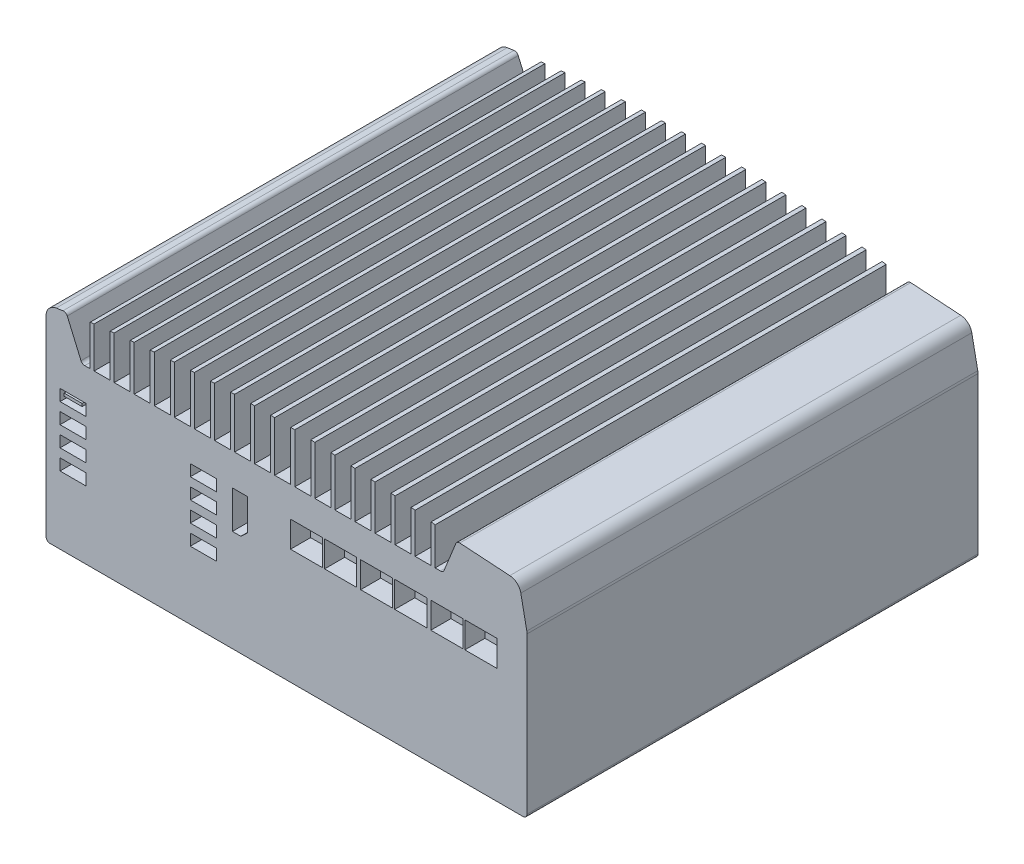
SolidWorks part; units mm, degrees
ref_plane "Plan de face" through (0, 0, 0) normal (0, 0, 1) x (1, 0, 0)
ref_plane "Plan de dessus" through (0, 0, 0) normal (0, 1, 0) x (1, 0, 0)
ref_plane "Plan de droite" through (0, 0, 0) normal (1, 0, 0) x (0, 0, -1)
sketch "Esquisse1" plane through (0, 0, 0) normal (0, 0, 1) x (1, 0, 0)
  line L0 (120, 110.504) -> (120, 0) construction
  line L1 (0, 0) -> (240, 0) construction
  line L2 (0, 0) -> (0, 110.5) construction
  line L3 (0, 110.5) -> (240, 110.5) construction
  line L4 (240, 0) -> (240, 110.5) construction
  line L5 (0, 0) -> (0, 102.5)
  line L6 (0, 102.5) -> (10, 103.9922)
  line L7 (10, 103.9922) -> (18, 85.5)
  line L8 (18, 85.5) -> (22, 85.5)
  line L9 (22, 85.5) -> (22, 105.5771)
  line L10 (22, 105.5771) -> (24, 105.8196)
  line L11 (24, 105.8196) -> (24, 85.5)
  line L12 (24, 85.5) -> (32, 85.5)
  line L13 (32, 85.5) -> (32, 106.7275)
  line L14 (32, 106.7275) -> (34.0035, 106.9395)
  line L15 (34.0035, 106.9395) -> (34.0035, 85.5)
  line L16 (34.0035, 85.5) -> (42.0035, 85.5)
  line L17 (42.0035, 85.5) -> (42.0035, 107.7243)
  line L18 (42.0035, 107.7243) -> (44.0099, 107.9057)
  line L19 (44.0099, 107.9057) -> (44.0099, 85.5)
  line L20 (44.0099, 85.5) -> (52.0099, 85.5)
  line L21 (62.0189, 85.5) -> (62.0189, 109.2586)
  line L22 (62.0189, 109.2586) -> (64.0299, 109.379)
  line L23 (64.0299, 109.379) -> (64.0299, 85.5)
  line L24 (54.0189, 85.5) -> (62.0189, 85.5)
  line L25 (52.0099, 85.5) -> (52.0099, 108.5678)
  line L26 (52.0099, 108.5678) -> (54.0189, 108.7187)
  line L27 (54.0189, 108.7187) -> (54.0189, 85.5)
  line L28 (64.0299, 85.5) -> (72.0299, 85.5)
  line L29 (72.0299, 85.5) -> (72.0299, 109.797)
  line L30 (72.0299, 109.797) -> (74.0426, 109.8868)
  line L31 (74.0426, 109.8868) -> (74.0426, 85.5)
  line L32 (74.0426, 85.5) -> (82.0426, 85.5)
  line L33 (82.0426, 85.5) -> (82.0426, 110.1832)
  line L34 (82.0426, 110.1832) -> (84.0563, 110.2425)
  line L35 (84.0563, 110.2425) -> (84.0563, 85.5)
  line L36 (84.0563, 85.5) -> (92.0563, 85.5)
  line L37 (92.0563, 110.4174) -> (94.0708, 110.4462)
  line L38 (94.0708, 110.4462) -> (94.0708, 85.5)
  line L39 (94.0708, 85.5) -> (102.0708, 85.5)
  line L40 (104.0854, 85.5) -> (112.0854, 85.5)
  line L41 (114.0998, 85.5) -> (122.0998, 85.5)
  line L42 (92.0563, 110.4174) -> (92.0563, 85.5)
  line L43 (124.1135, 85.5) -> (132.1135, 85.5)
  line L44 (102.0708, 85.5) -> (102.0708, 110.4999)
  line L45 (102.0708, 110.4999) -> (104.0854, 110.4981)
  line L46 (104.0854, 110.4981) -> (104.0854, 85.5)
  line L47 (144.1368, 85.5) -> (152.1368, 85.5)
  line L48 (122.0998, 85.5) -> (122.0998, 110.2092)
  line L49 (122.0998, 110.2092) -> (124.1135, 110.1464)
  line L50 (124.1135, 110.1464) -> (124.1135, 85.5)
  line L51 (152.1368, 85.5) -> (152.1368, 108.6326)
  line L52 (112.0854, 85.5) -> (112.0854, 110.4305)
  line L53 (112.0854, 110.4305) -> (114.0998, 110.3982)
  line L54 (114.0998, 110.3982) -> (114.0998, 85.5)
  line L55 (152.1368, 108.6326) -> (154.1455, 108.4782)
  line L56 (132.1135, 85.5) -> (132.1135, 109.8359)
  line L57 (132.1135, 109.8359) -> (134.1259, 109.7426)
  line L58 (134.1259, 109.7426) -> (134.1259, 85.5)
  line L59 (134.1259, 85.5) -> (142.1259, 85.5)
  line L60 (142.1259, 85.5) -> (142.1259, 109.3105)
  line L61 (142.1259, 109.3105) -> (144.1368, 109.1866)
  line L62 (144.1368, 109.1866) -> (144.1368, 85.5)
  line L63 (0, 85.5) -> (240, 85.5) construction
  line L64 (154.1455, 108.4782) -> (154.1455, 85.5)
  line L65 (154.1455, 85.5) -> (162.1455, 85.5)
  line L66 (162.1455, 85.5) -> (162.1455, 107.802)
  line L67 (162.1455, 107.802) -> (164.1516, 107.617)
  line L68 (164.1516, 107.617) -> (164.1516, 85.5)
  line L69 (164.1516, 85.5) -> (172.1516, 85.5)
  line L70 (172.1516, 85.5) -> (172.1516, 106.818)
  line L71 (172.1516, 106.818) -> (174.1547, 106.6026)
  line L72 (174.1547, 106.6026) -> (174.1547, 85.5)
  line L73 (174.1547, 85.5) -> (182.1547, 85.5)
  line L74 (182.1547, 85.5) -> (182.1547, 105.6804)
  line L75 (182.1547, 105.6804) -> (184.1543, 105.4344)
  line L76 (184.1543, 105.4344) -> (184.1543, 85.5)
  line L77 (184.1543, 85.5) -> (192.1543, 85.5)
  line L78 (192.1543, 85.5) -> (192.1543, 104.3883)
  line L79 (192.1543, 104.3883) -> (194.1498, 104.1119)
  line L80 (194.1498, 104.1119) -> (194.1498, 85.5)
  line L81 (194.1498, 85.5) -> (198.1498, 85.5)
  line L82 (0, 102.5) -> (240, 102.5) construction
  line L83 (198.1498, 85.5) -> (205, 102.5)
  line L84 (205, 102.5) -> (236, 100.5)
  line L85 (236, 100.5) -> (240, 80.5)
  line L86 (0, 0) -> (240, 0)
  line L87 (240, 0) -> (240, 80.5)
  line L88 (72, 69.5) -> (85, 69.5)
  line L89 (122, 70.5) -> (138, 70.5)
  line L90 (122, 70.5) -> (122, 57.5)
  line L91 (122, 57.5) -> (138, 57.5)
  line L92 (138, 70.5) -> (138, 57.5)
  line L93 (139, 70.5) -> (155, 70.5)
  line L94 (139, 70.5) -> (139, 57.5)
  line L95 (139, 57.5) -> (155, 57.5)
  line L96 (155, 70.5) -> (155, 57.5)
  line L97 (157, 70.5) -> (173, 70.5)
  line L98 (157, 70.5) -> (157, 57.5)
  line L99 (157, 57.5) -> (173, 57.5)
  line L100 (173, 70.5) -> (173, 57.5)
  line L101 (174, 70.5) -> (190, 70.5)
  line L102 (174, 70.5) -> (174, 57.5)
  line L103 (174, 57.5) -> (190, 57.5)
  line L104 (190, 70.5) -> (190, 57.5)
  line L105 (192, 70.5) -> (208, 70.5)
  line L106 (192, 70.5) -> (192, 57.5)
  line L107 (192, 57.5) -> (208, 57.5)
  line L108 (208, 70.5) -> (208, 57.5)
  line L109 (209, 70.5) -> (225, 70.5)
  line L110 (209, 70.5) -> (209, 57.5)
  line L111 (209, 57.5) -> (225, 57.5)
  line L112 (225, 70.5) -> (225, 57.5)
  line L117 (85, 69.5) -> (85, 63.8)
  line L118 (72, 63.8) -> (85, 63.8)
  line L119 (72, 69.5) -> (72, 63.8)
  line L120 (72, 59.5) -> (85, 59.5)
  line L121 (85, 59.5) -> (85, 53.8)
  line L122 (72, 53.8) -> (85, 53.8)
  line L123 (72, 59.5) -> (72, 53.8)
  line L124 (72, 49.5) -> (85, 49.5)
  line L125 (85, 49.5) -> (85, 43.8)
  line L126 (72, 43.8) -> (85, 43.8)
  line L127 (72, 49.5) -> (72, 43.8)
  line L128 (72, 39.5) -> (85, 39.5)
  line L129 (85, 39.5) -> (85, 33.8)
  line L130 (72, 33.8) -> (85, 33.8)
  line L131 (72, 39.5) -> (72, 33.8)
  line L132 (7, 59.5) -> (20, 59.5)
  line L133 (20, 59.5) -> (20, 53.8)
  line L134 (7, 53.8) -> (20, 53.8)
  line L135 (7, 59.5) -> (7, 53.8)
  line L136 (7, 49.5) -> (20, 49.5)
  line L137 (20, 49.5) -> (20, 43.8)
  line L138 (7, 43.8) -> (20, 43.8)
  line L139 (7, 49.5) -> (7, 43.8)
  line L140 (7, 39.5) -> (20, 39.5)
  line L141 (20, 39.5) -> (20, 33.8)
  line L142 (7, 33.8) -> (20, 33.8)
  line L143 (7, 39.5) -> (7, 33.8)
  line L144 (20.7134, 20.5694) -> (19.7134, 10.5694) construction
  line L145 (19.7134, 10.5694) -> (38.7134, 10.5694) construction
  line L146 (38.7134, 10.5694) -> (37.7134, 20.5694) construction
  line L147 (37.7134, 20.5694) -> (20.7134, 20.5694) construction
  line L148 (29.2134, 20.5694) -> (29.2134, 10.5694) construction
  line L149 (29.2134, 15.5694) -> (51.7399, 15.5694) construction
  line L150 (60.7134, 20.5694) -> (59.7134, 10.5694) construction
  line L151 (59.7134, 10.5694) -> (78.7134, 10.5694) construction
  line L152 (78.7134, 10.5694) -> (77.7134, 20.5694) construction
  line L153 (77.7134, 20.5694) -> (60.7134, 20.5694) construction
  line L154 (93, 69.5) -> (93, 50.7)
  line L155 (93, 50.7) -> (97.2, 50.7)
  line L156 (97.2, 50.7) -> (100.6, 53.8)
  line L157 (100.6, 53.8) -> (100.6, 69.5)
  line L158 (100.6, 69.5) -> (93, 69.5)
  arc A0 (0, 102.5) -> (172.1516, 106.818) centre (102.5, -550.1406) cw construction
  circle A1 centre (41.7134, 15.5694) radius 1.6 construction
  circle A2 centre (16.7134, 15.5694) radius 1.6 construction
  circle A3 centre (56.7134, 15.5694) radius 1.6 construction
  circle A4 centre (81.7134, 15.5694) radius 1.6 construction
  point P169 (85, 66.65)
  line B0 (7, 69.5) -> (20, 69.5)
  line B1 (7, 69.5) -> (7, 63.8)
  line B2 (7, 63.8) -> (20, 63.8)
  line B3 (20, 69.5) -> (20, 63.8)
  line B4 (9, 67.1) -> (18, 67.1)
  line B5 (9, 68.5) -> (9, 67.1)
  line B6 (9, 68.5) -> (18, 68.5)
  line B7 (18, 68.5) -> (18, 67.1)
  line B8 (13.5, 69.5) -> (13.5, 63.8) construction
  dimension "D28" = 3.2
  dimension "D1" = 110.5
  dimension "D2" = 240
  dimension "D3" = 8
  dimension "D4" = 2
  dimension "D5" = 25
  dimension "D6" = 10
  dimension "D7" = 4
  dimension "D8" = 4
  dimension "D9" = 16
  dimension "D10" = 1
  dimension "D11" = 1
  dimension "D12" = 1
  dimension "D13" = 2
  dimension "D14" = 2
  dimension "D15" = 13
  dimension "D16" = 15
  dimension "D17" = 15
  dimension "D22" = 10
  dimension "D23" = 65
  dimension "D24" = 19
  dimension "D25" = 17
  dimension "D26" = 10
  dimension "D27" = 25
  dimension "D29" = 18
  dimension "D30" = 10
  dimension "D31" = 4
  dimension "D32" = 35
  dimension "D33" = 2
  dimension "D35" = 5
  dimension "D36" = 18.8
  dimension "D37" = 4.2
  dimension "D38" = 7.6
  dimension "D39" = 15.7
  dimension "D40" = 1
  dimension "D41" = 7
  dimension "D42" = 8
  dimension "D34" = 2
sketch_block_instance "Bloc2-1"
sketch_block "Bloc2" parameters "D1"=13, "D2"=5.7, "D3"=9.5498, "D4"=1.2754, "D5"=9
extrude "Boss.-Extru.1" add sketch "Esquisse1" against normal blind 10 contours L86 L87 L85 L84 L83 L81 L80 L79 L78 L77 L76 L75 L74 L73 L72 L71 L70 L69 L68 L67 L66 L65 L64 L55 L51 L47 L62 L61 L60 L59 L58 L57 L56 L43 L50 L49 L48 L41 L54 L53 L52 L40 L46 L45 L44 L39 L38 L37 L42 L36 L35 | B7 B6 B5 B4
fillet "Congé1" radius 6 3 edges at (0, 102.5, -5) (240, 80.5, -5) (236, 100.5, -5)
fillet "Congé2" radius 2 6 edges at (0, 0, -5) (240, 0, -5) (198.1498, 85.5, -5) (205, 102.5, -5) (18, 85.5, -5) (10, 103.9922, -5)
sketch "Esquisse2" plane through (0, 0, -10) normal (0, 0, -1) x (-1, 0, 0)
  line L174 (-198.6545, 86.7525) -> (-204.4595, 101.1585)
  line L175 (-206.4433, 102.4069) -> (-231.4057, 100.7964)
  line L176 (-236.9029, 95.9856) -> (-239.8835, 81.0826)
  line L177 (-240, 79.9059) -> (-240, 2)
  line L178 (-238, 0) -> (-2, 0)
  line L179 (0, 2) -> (0, 97.3289)
  line L180 (-5.1145, 103.2632) -> (-8.4796, 103.7653)
  line L181 (-10.6104, 102.5814) -> (-17.4783, 86.7059)
  line L182 (-19.3139, 85.5) -> (-22, 85.5)
  line L183 (-22, 85.5) -> (-22, 105.5771)
  line L184 (-22, 105.5771) -> (-24, 105.8196)
  line L185 (-24, 105.8196) -> (-24, 85.5)
  line L186 (-24, 85.5) -> (-32, 85.5)
  line L187 (-32, 85.5) -> (-32, 106.7275)
  line L188 (-32, 106.7275) -> (-34.0035, 106.9395)
  line L189 (-34.0035, 106.9395) -> (-34.0035, 85.5)
  line L190 (-34.0035, 85.5) -> (-42.0035, 85.5)
  line L191 (-42.0035, 85.5) -> (-42.0035, 107.7243)
  line L192 (-42.0035, 107.7243) -> (-44.0099, 107.9057)
  line L193 (-44.0099, 107.9057) -> (-44.0099, 85.5)
  line L194 (-44.0099, 85.5) -> (-52.0099, 85.5)
  line L195 (-52.0099, 85.5) -> (-52.0099, 108.5678)
  line L196 (-52.0099, 108.5678) -> (-54.0189, 108.7187)
  line L197 (-54.0189, 108.7187) -> (-54.0189, 85.5)
  line L198 (-54.0189, 85.5) -> (-62.0189, 85.5)
  line L199 (-62.0189, 85.5) -> (-62.0189, 109.2586)
  line L200 (-62.0189, 109.2586) -> (-64.0299, 109.379)
  line L201 (-64.0299, 109.379) -> (-64.0299, 85.5)
  line L202 (-64.0299, 85.5) -> (-72.0299, 85.5)
  line L203 (-72.0299, 85.5) -> (-72.0299, 109.797)
  line L204 (-72.0299, 109.797) -> (-74.0426, 109.8868)
  line L205 (-74.0426, 109.8868) -> (-74.0426, 85.5)
  line L206 (-74.0426, 85.5) -> (-82.0426, 85.5)
  line L207 (-82.0426, 85.5) -> (-82.0426, 110.1832)
  line L208 (-82.0426, 110.1832) -> (-84.0563, 110.2425)
  line L209 (-84.0563, 110.2425) -> (-84.0563, 85.5)
  line L210 (-84.0563, 85.5) -> (-92.0563, 85.5)
  line L211 (-92.0563, 85.5) -> (-92.0563, 110.4174)
  line L212 (-92.0563, 110.4174) -> (-94.0708, 110.4462)
  line L213 (-94.0708, 110.4462) -> (-94.0708, 85.5)
  line L214 (-94.0708, 85.5) -> (-102.0708, 85.5)
  line L215 (-102.0708, 85.5) -> (-102.0708, 110.4999)
  line L216 (-102.0708, 110.4999) -> (-104.0854, 110.4981)
  line L217 (-104.0854, 110.4981) -> (-104.0854, 85.5)
  line L218 (-104.0854, 85.5) -> (-112.0854, 85.5)
  line L219 (-112.0854, 85.5) -> (-112.0854, 110.4305)
  line L220 (-112.0854, 110.4305) -> (-114.0998, 110.3982)
  line L221 (-114.0998, 110.3982) -> (-114.0998, 85.5)
  line L222 (-114.0998, 85.5) -> (-122.0998, 85.5)
  line L223 (-122.0998, 85.5) -> (-122.0998, 110.2092)
  line L224 (-122.0998, 110.2092) -> (-124.1135, 110.1464)
  line L225 (-124.1135, 110.1464) -> (-124.1135, 85.5)
  line L226 (-124.1135, 85.5) -> (-132.1135, 85.5)
  line L227 (-132.1135, 85.5) -> (-132.1135, 109.8359)
  line L228 (-132.1135, 109.8359) -> (-134.1259, 109.7426)
  line L229 (-134.1259, 109.7426) -> (-134.1259, 85.5)
  line L230 (-134.1259, 85.5) -> (-142.1259, 85.5)
  line L231 (-142.1259, 85.5) -> (-142.1259, 109.3105)
  line L232 (-142.1259, 109.3105) -> (-144.1368, 109.1866)
  line L233 (-144.1368, 109.1866) -> (-144.1368, 85.5)
  line L234 (-144.1368, 85.5) -> (-152.1368, 85.5)
  line L235 (-152.1368, 85.5) -> (-152.1368, 108.6326)
  line L236 (-152.1368, 108.6326) -> (-154.1455, 108.4782)
  line L237 (-154.1455, 108.4782) -> (-154.1455, 85.5)
  line L238 (-154.1455, 85.5) -> (-162.1455, 85.5)
  line L239 (-162.1455, 85.5) -> (-162.1455, 107.802)
  line L240 (-162.1455, 107.802) -> (-164.1516, 107.617)
  line L241 (-164.1516, 107.617) -> (-164.1516, 85.5)
  line L242 (-164.1516, 85.5) -> (-172.1516, 85.5)
  line L243 (-172.1516, 85.5) -> (-172.1516, 106.818)
  line L244 (-172.1516, 106.818) -> (-174.1547, 106.6026)
  line L245 (-174.1547, 106.6026) -> (-174.1547, 85.5)
  line L246 (-174.1547, 85.5) -> (-182.1547, 85.5)
  line L247 (-182.1547, 85.5) -> (-182.1547, 105.6804)
  line L248 (-182.1547, 105.6804) -> (-184.1543, 105.4344)
  line L249 (-184.1543, 105.4344) -> (-184.1543, 85.5)
  line L250 (-184.1543, 85.5) -> (-192.1543, 85.5)
  line L251 (-192.1543, 85.5) -> (-192.1543, 104.3883)
  line L252 (-192.1543, 104.3883) -> (-194.1498, 104.1119)
  line L253 (-194.1498, 104.1119) -> (-194.1498, 85.5)
  line L254 (-194.1498, 85.5) -> (-196.7995, 85.5)
  line L255 (-198.6545, 86.7525) -> (-204.4595, 101.1585)
  line L256 (-206.4433, 102.4069) -> (-231.4057, 100.7964)
  line L257 (-236.9029, 95.9856) -> (-239.8835, 81.0826)
  line L258 (-240, 79.9059) -> (-240, 2)
  line L259 (-238, 0) -> (-2, 0)
  line L260 (0, 2) -> (0, 97.3289)
  line L261 (-5.1145, 103.2632) -> (-8.4796, 103.7653)
  line L262 (-10.6104, 102.5814) -> (-17.4783, 86.7059)
  line L263 (-19.3139, 85.5) -> (-22, 85.5)
  line L264 (-22, 85.5) -> (-22, 105.5771)
  line L265 (-22, 105.5771) -> (-24, 105.8196)
  line L266 (-24, 105.8196) -> (-24, 85.5)
  line L267 (-24, 85.5) -> (-32, 85.5)
  line L268 (-32, 85.5) -> (-32, 106.7275)
  line L269 (-32, 106.7275) -> (-34.0035, 106.9395)
  line L270 (-34.0035, 106.9395) -> (-34.0035, 85.5)
  line L271 (-34.0035, 85.5) -> (-42.0035, 85.5)
  line L272 (-42.0035, 85.5) -> (-42.0035, 107.7243)
  line L273 (-42.0035, 107.7243) -> (-44.0099, 107.9057)
  line L274 (-44.0099, 107.9057) -> (-44.0099, 85.5)
  line L275 (-44.0099, 85.5) -> (-52.0099, 85.5)
  line L276 (-52.0099, 85.5) -> (-52.0099, 108.5678)
  line L277 (-52.0099, 108.5678) -> (-54.0189, 108.7187)
  line L278 (-54.0189, 108.7187) -> (-54.0189, 85.5)
  line L279 (-54.0189, 85.5) -> (-62.0189, 85.5)
  line L280 (-62.0189, 85.5) -> (-62.0189, 109.2586)
  line L281 (-62.0189, 109.2586) -> (-64.0299, 109.379)
  line L282 (-64.0299, 109.379) -> (-64.0299, 85.5)
  line L283 (-64.0299, 85.5) -> (-72.0299, 85.5)
  line L284 (-72.0299, 85.5) -> (-72.0299, 109.797)
  line L285 (-72.0299, 109.797) -> (-74.0426, 109.8868)
  line L286 (-74.0426, 109.8868) -> (-74.0426, 85.5)
  line L287 (-74.0426, 85.5) -> (-82.0426, 85.5)
  line L288 (-82.0426, 85.5) -> (-82.0426, 110.1832)
  line L289 (-82.0426, 110.1832) -> (-84.0563, 110.2425)
  line L290 (-84.0563, 110.2425) -> (-84.0563, 85.5)
  line L291 (-84.0563, 85.5) -> (-92.0563, 85.5)
  line L292 (-92.0563, 85.5) -> (-92.0563, 110.4174)
  line L293 (-92.0563, 110.4174) -> (-94.0708, 110.4462)
  line L294 (-94.0708, 110.4462) -> (-94.0708, 85.5)
  line L295 (-94.0708, 85.5) -> (-102.0708, 85.5)
  line L296 (-102.0708, 85.5) -> (-102.0708, 110.4999)
  line L297 (-102.0708, 110.4999) -> (-104.0854, 110.4981)
  line L298 (-104.0854, 110.4981) -> (-104.0854, 85.5)
  line L299 (-104.0854, 85.5) -> (-112.0854, 85.5)
  line L300 (-112.0854, 85.5) -> (-112.0854, 110.4305)
  line L301 (-112.0854, 110.4305) -> (-114.0998, 110.3982)
  line L302 (-114.0998, 110.3982) -> (-114.0998, 85.5)
  line L303 (-114.0998, 85.5) -> (-122.0998, 85.5)
  line L304 (-122.0998, 85.5) -> (-122.0998, 110.2092)
  line L305 (-122.0998, 110.2092) -> (-124.1135, 110.1464)
  line L306 (-124.1135, 110.1464) -> (-124.1135, 85.5)
  line L307 (-124.1135, 85.5) -> (-132.1135, 85.5)
  line L308 (-132.1135, 85.5) -> (-132.1135, 109.8359)
  line L309 (-132.1135, 109.8359) -> (-134.1259, 109.7426)
  line L310 (-134.1259, 109.7426) -> (-134.1259, 85.5)
  line L311 (-134.1259, 85.5) -> (-142.1259, 85.5)
  line L312 (-142.1259, 85.5) -> (-142.1259, 109.3105)
  line L313 (-142.1259, 109.3105) -> (-144.1368, 109.1866)
  line L314 (-144.1368, 109.1866) -> (-144.1368, 85.5)
  line L315 (-144.1368, 85.5) -> (-152.1368, 85.5)
  line L316 (-152.1368, 85.5) -> (-152.1368, 108.6326)
  line L317 (-152.1368, 108.6326) -> (-154.1455, 108.4782)
  line L318 (-154.1455, 108.4782) -> (-154.1455, 85.5)
  line L319 (-154.1455, 85.5) -> (-162.1455, 85.5)
  line L320 (-162.1455, 85.5) -> (-162.1455, 107.802)
  line L321 (-162.1455, 107.802) -> (-164.1516, 107.617)
  line L322 (-164.1516, 107.617) -> (-164.1516, 85.5)
  line L323 (-164.1516, 85.5) -> (-172.1516, 85.5)
  line L324 (-172.1516, 85.5) -> (-172.1516, 106.818)
  line L325 (-172.1516, 106.818) -> (-174.1547, 106.6026)
  line L326 (-174.1547, 106.6026) -> (-174.1547, 85.5)
  line L327 (-174.1547, 85.5) -> (-182.1547, 85.5)
  line L328 (-182.1547, 85.5) -> (-182.1547, 105.6804)
  line L329 (-182.1547, 105.6804) -> (-184.1543, 105.4344)
  line L330 (-184.1543, 105.4344) -> (-184.1543, 85.5)
  line L331 (-184.1543, 85.5) -> (-192.1543, 85.5)
  line L332 (-192.1543, 85.5) -> (-192.1543, 104.3883)
  line L333 (-192.1543, 104.3883) -> (-194.1498, 104.1119)
  line L334 (-194.1498, 104.1119) -> (-194.1498, 85.5)
  line L335 (-194.1498, 85.5) -> (-196.7995, 85.5)
  arc A33 (-204.4595, 101.1585) -> (-206.4433, 102.4069) centre (-206.3145, 100.411) ccw
  arc A34 (-231.4057, 100.7964) -> (-236.9029, 95.9856) centre (-231.0194, 94.8089) ccw
  arc A35 (-239.8835, 81.0826) -> (-240, 79.9059) centre (-234, 79.9059) ccw
  arc A36 (-240, 2) -> (-238, 0) centre (-238, 2) ccw
  arc A37 (-2, 0) -> (0, 2) centre (-2, 2) ccw
  arc A38 (0, 97.3289) -> (-5.1145, 103.2632) centre (-6, 97.3289) ccw
  arc A39 (-8.4796, 103.7653) -> (-10.6104, 102.5814) centre (-8.7748, 101.7872) ccw
  arc A40 (-19.3139, 85.5) -> (-17.4783, 86.7059) centre (-19.3139, 87.5) ccw
  arc A41 (-198.6545, 86.7525) -> (-196.7995, 85.5) centre (-196.7995, 87.5) ccw
  arc A42 (-204.4595, 101.1585) -> (-206.4433, 102.4069) centre (-206.3145, 100.411) ccw
  arc A43 (-231.4057, 100.7964) -> (-236.9029, 95.9856) centre (-231.0194, 94.8089) ccw
  arc A44 (-239.8835, 81.0826) -> (-240, 79.9059) centre (-234, 79.9059) ccw
  arc A45 (-240, 2) -> (-238, 0) centre (-238, 2) ccw
  arc A46 (-2, 0) -> (0, 2) centre (-2, 2) ccw
  arc A47 (0, 97.3289) -> (-5.1145, 103.2632) centre (-6, 97.3289) ccw
  arc A48 (-8.4796, 103.7653) -> (-10.6104, 102.5814) centre (-8.7748, 101.7872) ccw
  arc A49 (-19.3139, 85.5) -> (-17.4783, 86.7059) centre (-19.3139, 87.5) ccw
  arc A50 (-198.6545, 86.7525) -> (-196.7995, 85.5) centre (-196.7995, 87.5) ccw
  dimension "D1" = 0
extrude "Boss.-Extru.2" add sketch "Esquisse2" along normal blind 215
sketch "Esquisse3" plane through (0, 0, -225) normal (0, 0, -1) x (-1, 0, 0)
  line L4 (0, 2) -> (0, 97.3289) construction
  line L36 (-29, 43.5) -> (-5, 43.5)
  line L37 (-29, 63.5) -> (-5, 63.5)
  line L38 (-29, 63.5) -> (-29, 71.5)
  line L39 (-29, 71.5) -> (-5, 71.5)
  line L40 (-5, 63.5) -> (-5, 71.5)
  line L41 (-5, 43.5) -> (-5, 51.5)
  line L42 (-29, 51.5) -> (-5, 51.5)
  line L43 (-29, 43.5) -> (-29, 51.5)
  line B0 (-58.1801, 68.699) -> (-58.7801, 62.699)
  line B1 (-56.79, 60.5) -> (-42.21, 60.5)
  line B2 (-40.2199, 62.699) -> (-40.8199, 68.699)
  line B3 (-42.81, 70.5) -> (-56.19, 70.5)
  line B4 (-49.5, 70.5) -> (-49.5, 60.5) construction
  line B5 (-49.5, 65.5) -> (-37, 65.5) construction
  circle B6 centre (-37, 65.5) radius 1.6
  circle B7 centre (-62, 65.5) radius 1.6
  arc B8 (-58.7801, 62.699) -> (-56.79, 60.5) centre (-56.79, 62.5) ccw
  arc B9 (-42.21, 60.5) -> (-40.2199, 62.699) centre (-42.21, 62.5) ccw
  arc B10 (-40.8199, 68.699) -> (-42.81, 70.5) centre (-42.81, 68.5) ccw
  arc B11 (-56.19, 70.5) -> (-58.1801, 68.699) centre (-56.19, 68.5) ccw
  line B12 (-138.1801, 68.699) -> (-138.7801, 62.699)
  line B13 (-136.79, 60.5) -> (-122.21, 60.5)
  line B14 (-120.2199, 62.699) -> (-120.8199, 68.699)
  line B15 (-122.81, 70.5) -> (-136.19, 70.5)
  line B16 (-129.5, 70.5) -> (-129.5, 60.5) construction
  circle B17 centre (-117, 65.5) radius 1.6
  circle B18 centre (-142, 65.5) radius 1.6
  arc B19 (-138.7801, 62.699) -> (-136.79, 60.5) centre (-136.79, 62.5) ccw
  arc B20 (-122.21, 60.5) -> (-120.2199, 62.699) centre (-122.21, 62.5) ccw
  arc B21 (-120.8199, 68.699) -> (-122.81, 70.5) centre (-122.81, 68.5) ccw
  arc B22 (-136.19, 70.5) -> (-138.1801, 68.699) centre (-136.19, 68.5) ccw
  line B23 (-98.1801, 68.699) -> (-98.7801, 62.699)
  line B24 (-96.79, 60.5) -> (-82.21, 60.5)
  line B25 (-80.2199, 62.699) -> (-80.8199, 68.699)
  line B26 (-82.81, 70.5) -> (-96.19, 70.5)
  line B27 (-89.5, 70.5) -> (-89.5, 60.5) construction
  circle B28 centre (-77, 65.5) radius 1.6
  circle B29 centre (-102, 65.5) radius 1.6
  arc B30 (-98.7801, 62.699) -> (-96.79, 60.5) centre (-96.79, 62.5) ccw
  arc B31 (-82.21, 60.5) -> (-80.2199, 62.699) centre (-82.21, 62.5) ccw
  arc B32 (-80.8199, 68.699) -> (-82.81, 70.5) centre (-82.81, 68.5) ccw
  arc B33 (-96.19, 70.5) -> (-98.1801, 68.699) centre (-96.19, 68.5) ccw
  line B34 (-58.1801, 48.699) -> (-58.7801, 42.699)
  line B35 (-56.79, 40.5) -> (-42.21, 40.5)
  line B36 (-40.2199, 42.699) -> (-40.8199, 48.699)
  line B37 (-42.81, 50.5) -> (-56.19, 50.5)
  line B38 (-49.5, 50.5) -> (-49.5, 40.5) construction
  line B39 (-49.5, 45.5) -> (-37, 45.5) construction
  circle B40 centre (-37, 45.5) radius 1.6
  circle B41 centre (-62, 45.5) radius 1.6
  arc B42 (-58.7801, 42.699) -> (-56.79, 40.5) centre (-56.79, 42.5) ccw
  arc B43 (-42.21, 40.5) -> (-40.2199, 42.699) centre (-42.21, 42.5) ccw
  arc B44 (-40.8199, 48.699) -> (-42.81, 50.5) centre (-42.81, 48.5) ccw
  arc B45 (-56.19, 50.5) -> (-58.1801, 48.699) centre (-56.19, 48.5) ccw
  dimension "D5" = 5
  dimension "D2" = 40
  dimension "D3" = 40
  dimension "D4" = 20
  dimension "D15" = 8
  dimension "D16" = 1
  dimension "D17" = 24
  dimension "D19" = 20
  dimension "D18" = 2
sketch_block_instance "Bloc1-1"
sketch_block "Bloc1" parameters "D5"=3.2, "D6"=2, "D1"=25, "D2"=17, "D3"=19, "D4"=10
sketch_block_instance "Bloc1-2"
sketch_block_instance "Bloc1-3"
sketch_block_instance "Bloc1-4"
extrude "Enlèv. mat.-Extru.1" cut sketch "Esquisse3" against normal blind 10
sketch "Esquisse4" plane through (0, 0, 0) normal (0, -1, 0) x (1, 0, 0)
  line L2 (240, 0) -> (240, -225) construction
  line L3 (238, -225) -> (2, -225) construction
  line B0 (228, -200) -> (228, -25) construction
  line B1 (240, 0) -> (240, -225) construction
  line B2 (240, -225) -> (0, -225) construction
  line B3 (228, -112.5) -> (0, -112.5) construction
  circle B4 centre (228, -200) radius 1.65
  circle B5 centre (228, -25) radius 1.65
  circle B6 centre (12, -200) radius 1.65
  circle B7 centre (12, -25) radius 1.65
  line B8 (12, -200) -> (12, -25) construction
sketch_block_instance "Insert_PC_Neousys-1"
sketch_block "Insert_PC_Neousys" parameters "D6"=3.3, "D1"=185, "D2"=35, "D3"=35, "D4"=216, "D5"=175, "D7"=12, "D8"=25, "D9"=12, "D10"=60, "D11"=30
extrude "Enlèv. mat.-Extru.2" cut sketch "Esquisse4" against normal blind 10
